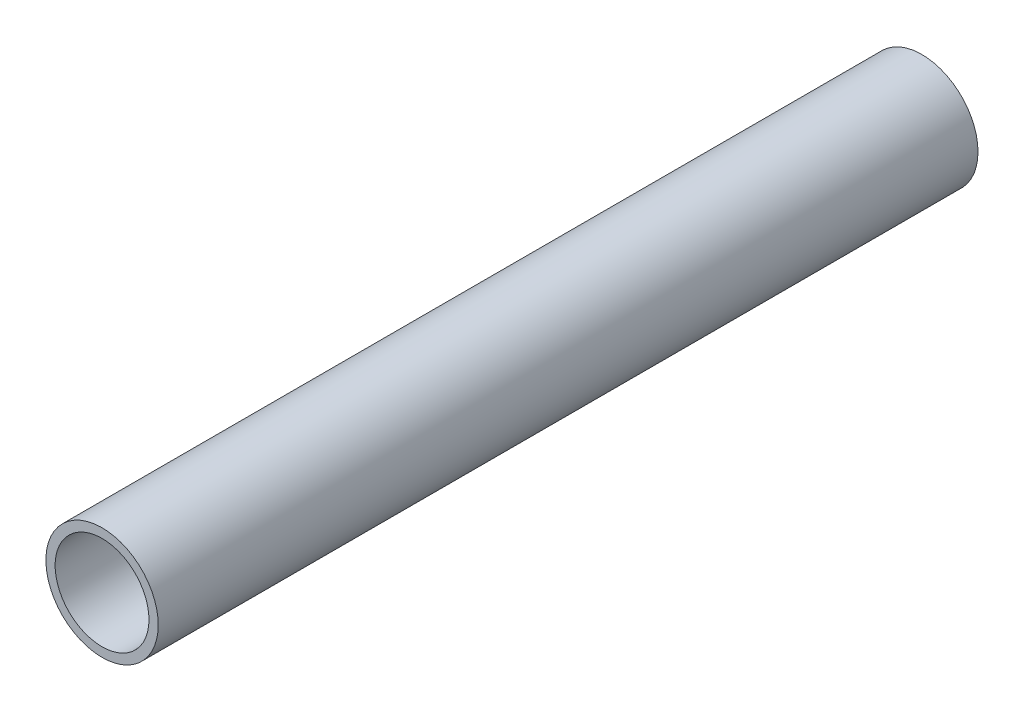
SolidWorks part; units mm, degrees
ref_plane "Front Plane" through (0, 0, 0) normal (0, 0, 1) x (1, 0, 0)
ref_plane "Top Plane" through (0, 0, 0) normal (0, 1, 0) x (1, 0, 0)
ref_plane "Right Plane" through (0, 0, 0) normal (1, 0, 0) x (0, 0, -1)
sketch "Sketch2" plane through (0, 0, 0) normal (0, 0, 1) x (1, 0, 0)
  circle A0 centre (0, 0) radius 16.4099
  circle A1 centre (0, 0) radius 13.7108
extrude "Boss-Extrude1" add sketch "Sketch2" along normal blind 239.522
